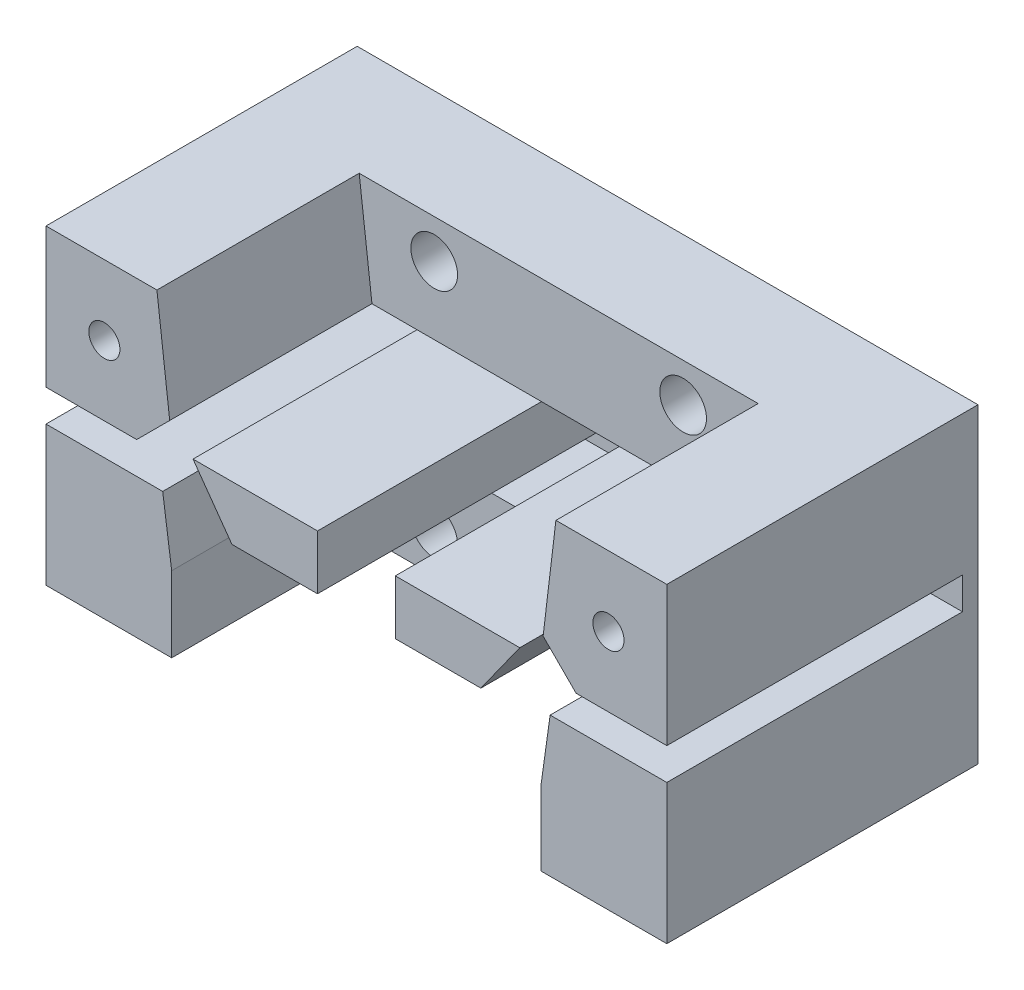
SolidWorks part; units mm, degrees
ref_plane "前视基准面" through (0, 0, 0) normal (0, 0, 1) x (1, 0, 0)
ref_plane "上视基准面" through (0, 0, 0) normal (0, 1, 0) x (1, 0, 0)
ref_plane "右视基准面" through (0, 0, 0) normal (1, 0, 0) x (0, 0, -1)
sketch "草图1" plane through (0, 0, 0) normal (0, 0, 1) x (1, 0, 0)
  line L0 (0, 0) -> (27.195, 0) construction
  line L1 (0, 0) -> (0, 19.7925) construction
  line L3 (19.95, -10) -> (-19.95, -10)
  line L4 (19.95, -10) -> (19.95, 10)
  line L5 (19.95, 10) -> (-19.95, 10)
  line L6 (-19.95, -10) -> (-19.95, 10)
  line L7 (19.95, -10) -> (-19.95, 10) construction
  line L8 (19.95, 10) -> (-19.95, -10) construction
  point P1 (0, 0)
  dimension "D1" = 39.9
  dimension "D2" = 20
extrude "凸台-拉伸1" add sketch "草图1" along normal blind 1
sketch "草图2" plane through (0, 0, 1) normal (0, 0, 1) x (1, 0, 0)
  line L0 (0, 0) -> (27.0471, 0) construction
  line L1 (0, 0) -> (0, 13.3944) construction
  line L2 (-10.5, 1.75) -> (-2.5, 1.75)
  line L3 (-2.5, 1.75) -> (-2.5, -1.75)
  line L4 (-2.5, -1.75) -> (-8, -1.75)
  line L5 (-8, -1.75) -> (-10.5, 1.75)
  line L11 (-19.95, -1.025) -> (-12.45, -1.025)
  line L16 (2.5, 1.75) -> (10.5, 1.75)
  line L25 (10.5, 1.75) -> (8, -1.75)
  line L26 (8, -1.75) -> (2.5, -1.75)
  line L27 (2.5, -1.75) -> (2.5, 1.75)
  line L35 (-12.45, -1.025) -> (-10.6464, -3.55)
  line L36 (-10.6464, -3.55) -> (10.6464, -3.55)
  line L38 (-19.95, 1.025) -> (-14.1213, 1.025)
  line L39 (19.95, -10) -> (-19.95, -10)
  line L40 (-19.95, -10) -> (-19.95, -1.025)
  line L41 (-19.95, 10) -> (-19.95, -10) construction
  line L43 (19.95, -10) -> (19.95, -1.025)
  line L44 (12.45, -1.025) -> (10.6464, -3.55)
  line L45 (19.95, -1.025) -> (12.45, -1.025)
  line L46 (-14.1213, 1.025) -> (-12, 3.1463)
  line L47 (-12, 3.1463) -> (12, 3.1463)
  line L48 (0, 3.1463) -> (0, 10)
  line L49 (19.95, 10) -> (-19.95, 10)
  line L50 (19.95, 10) -> (-19.95, 10) construction
  line L51 (-19.95, 10) -> (-19.95, 1.025)
  line L52 (14.1213, 1.025) -> (12, 3.1463)
  line L53 (19.95, 1.025) -> (14.1213, 1.025)
  line L54 (19.95, 10) -> (19.95, 1.025)
  line M1 (-19.95, 10) -> (-19.95, -10)
  line M2 (-19.95, -10) -> (19.95, -10)
  line M3 (19.95, -10) -> (19.95, 10)
  line M4 (19.95, 10) -> (-19.95, 10)
  dimension "D1" = 8
  dimension "D2" = 3.5
  dimension "D3" = 5.5
  dimension "D4" = 1.75
  dimension "D5" = 2.5
  dimension "D6" = 7.5
  dimension "D7" = 1.8
  dimension "D8" = 1.025
  dimension "D9" = 1.025
  dimension "D10" = 2.5
  dimension "D11" = 5.5
  dimension "D12" = 8
  dimension "D13" = 3
  dimension "D14" = 12
  dimension "D15" = 225
extrude "凸台-拉伸4" add sketch "草图2" along normal blind 19 contours L47 L48 L38 L46 M4 M1 | L53 L48 L47 L52 M3 M4 | L5 L4 L3 L2 | L27 L26 L25 L16 | L45 L44 L36 L35 L11 M3 M1 M2
sketch "草图4" plane through (0, 0, 20) normal (0, 0, 1) x (1, 0, 0)
  line L4 (0, 0) -> (0, 14.9682) construction
  line L32 (-12.45, -1.025) -> (-11.1935, -10)
  line L33 (-19.95, -10) -> (19.95, -10) construction
  line L34 (-11.1935, -10) -> (0, -13.3875)
  line L37 (10.6464, -3.55) -> (-10.6464, -3.55)
  line L38 (-10.6464, -3.55) -> (-12.45, -1.025)
  line L39 (10.6464, -3.55) -> (12.45, -1.025)
  line L40 (11.1935, -10) -> (0, -13.3875)
  line L41 (12.45, -1.025) -> (11.1935, -10)
  line L42 (-14.1213, 1.025) -> (-12.45, 12.5639)
  line L43 (-12.45, 12.5639) -> (12.45, 12.5639)
  line L46 (-12, 3.1463) -> (-14.1213, 1.025)
  line L47 (12, 3.1463) -> (14.1213, 1.025)
  line L49 (14.1213, 1.025) -> (12.45, 12.5639)
  line L50 (-12, 3.1463) -> (12, 3.1463)
  dimension "D1" = 24.9
  dimension "D2" = 11.5389
extrude "切除-拉伸1" cut sketch "草图4" against normal blind 13
sketch "草图23" plane through (0, -10, 0) normal (0, -1, 0) x (1, 0, 0)
  line L0 (0, 0) -> (0, 24.6134) construction
  line L5 (-19.95, 20) -> (-11.1935, 20) construction
  point P0 (-15.5, 16)
  point P2 (-15.5, 4)
  dimension "D1" = 12
  dimension "D2" = 15.5
  dimension "D3" = 4
hole_wizard "Ø3.0mm 暗销孔3" positions "草图23" profile "草图22" hole size "Ø3.0" standard "BSI"
sketch "草图22" plane through (-15.5, -10, 16) normal (1, 0, 0) x (0, 0, -1)
  line L0 (0, 0) -> (0, 6.9013)
  line L1 (0, 6.9013) -> (1.5, 6)
  line L2 (1.5, 6) -> (1.5, 0)
  line L5 (1.5, 0) -> (0, 0)
  line L10 (0, 6.9013) -> (-1.5, 6) construction
  line L11 (0, -6.35) -> (0, 107.95) construction
  dimension "孔直径" = 3
  dimension "孔深度" = 6
  dimension "导头角度" = 118
mirror "镜向3" about plane through (0, 0, 0) normal (1, 0, 0) of "Ø3.0mm 暗销孔3"
sketch "草图25" plane through (0, 0, 7) normal (0, 0, 1) x (1, 0, 0)
  line L0 (-12.8214, 10) -> (-12, 3.1463)
  line L1 (-12, 3.1463) -> (-14.1213, 1.025)
  line L2 (-14.1213, 1.025) -> (-12.8214, 10)
  line L3 (0, -11) -> (0, 11) construction
  line L4 (12, 3.1463) -> (14.1213, 1.025)
  line L5 (14.1213, 1.025) -> (12.8214, 10)
  line L6 (12.8214, 10) -> (12, 3.1463)
extrude "凸台-拉伸5" add sketch "草图25" along normal blind 13
sketch "草图26" plane through (0, 0, 20) normal (0, 0, 1) x (1, 0, 0)
  line L0 (-11.8725, -5.15) -> (-11.8725, -10)
  line L1 (-12.45, -1.025) -> (-11.1935, -10) construction
  line L2 (-19.95, -10) -> (-11.1935, -10) construction
  line L3 (-11.8725, -10) -> (-11.1935, -10)
  line L4 (-11.1935, -10) -> (-11.8725, -5.15)
  line L5 (0, -11) -> (0, 11) construction
  line L6 (11.1935, -10) -> (11.8725, -5.15)
  line L7 (11.8725, -10) -> (11.1935, -10)
  line L8 (11.8725, -5.15) -> (11.8725, -10)
  dimension "D1" = 4.85
extrude "切除-拉伸2" cut sketch "草图26" against normal blind 13
sketch "草图27" plane through (0, 0, 20) normal (0, 0, 1) x (1, 0, 0)
  line L0 (0, 0) -> (23.5978, 0) construction
  line L1 (0, 0) -> (0, 15.9041) construction
  line L2 (-19.95, 10) -> (-19.95, 1.025) construction
  line L3 (-12.8214, 10) -> (-19.95, 10) construction
  circle A0 centre (-16.2, 5.5) radius 1
  circle A4 centre (16.2, 5.5) radius 1
  dimension "D1" = 2
  dimension "D2" = 3.75
  dimension "D3" = 4.5
extrude "切除-拉伸3" cut sketch "草图27" against normal blind 6
sketch "草图28" plane through (0, 0, 7) normal (0, 0, 1) x (1, 0, 0)
  line L0 (0, 0.9225) -> (0, 14.2804) construction
  line L1 (12.8214, 10) -> (-12.8214, 10) construction
  line L2 (-11.8725, -10) -> (11.8725, -10) construction
  circle A0 centre (-8, 7.5) radius 1.5
  circle A1 centre (-8, -7.5) radius 1.5
  circle A2 centre (8, -7.5) radius 1.5
  circle A3 centre (8, 7.5) radius 1.5
  dimension "D5" = 3
  dimension "D6" = 3
  dimension "D1" = 8
  dimension "D2" = 2.5
  dimension "D3" = 8
  dimension "D4" = 2.5
extrude "切除-拉伸4" cut sketch "草图28" against normal through all
